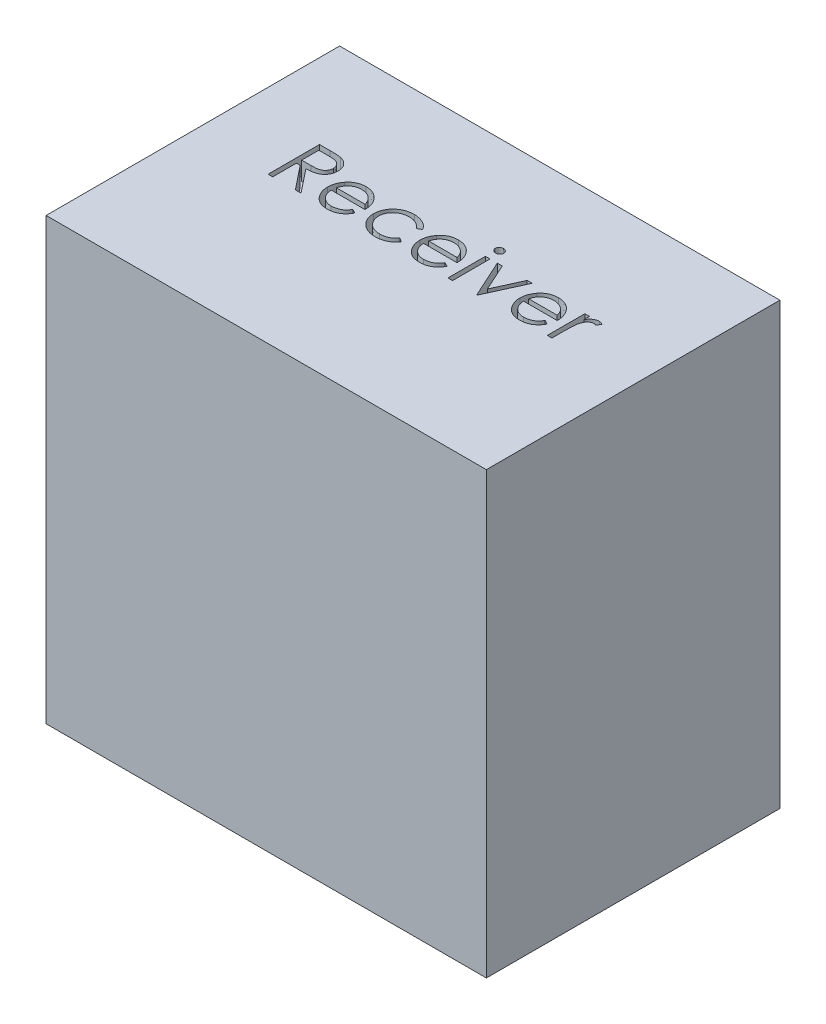
SolidWorks part; units mm, degrees
ref_plane "Front Plane" through (0, 0, 0) normal (0, 0, 1) x (1, 0, 0)
ref_plane "Top Plane" through (0, 0, 0) normal (0, 1, 0) x (1, 0, 0)
ref_plane "Right Plane" through (0, 0, 0) normal (1, 0, 0) x (0, 0, -1)
sketch "Sketch1" plane through (0, 0, 0) normal (0, 1, 0) x (1, 0, 0)
  line L1 (0, 0) -> (30, 0)
  line L2 (0, 0) -> (0, 20)
  line L3 (0, 20) -> (30, 20)
  line L4 (30, 0) -> (30, 20)
  dimension "D1" = 30
  dimension "D2" = 20
extrude "Boss-Extrude1" add sketch "Sketch1" along normal blind 30
sketch "Sketch2" plane through (0, 30, 0) normal (0, 1, 0) x (1, 0, 0)
  line L0 (0, 10) -> (30, 10) construction
  line L1 (0, 20) -> (0, 0) construction
  line L2 (30, 0) -> (30, 20) construction
  text T0 "Receiver"
extrude "Cut-Extrude1" cut sketch "Sketch2" against normal blind 1.27
